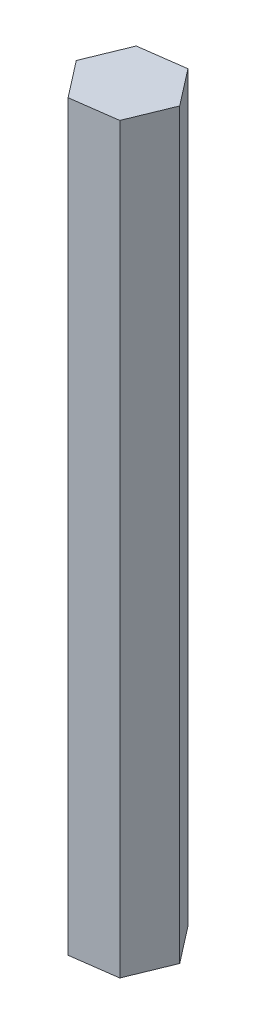
SolidWorks part; units mm, degrees
ref_plane "Front" through (0, 0, 0) normal (0, 0, 1) x (1, 0, 0)
ref_plane "Top" through (0, 0, 0) normal (0, 1, 0) x (1, 0, 0)
ref_plane "Right" through (0, 0, 0) normal (1, 0, 0) x (0, 0, -1)
sketch "Sketch1" plane through (0, 0, 0) normal (0, 1, 0) x (1, 0, 0)
  line L1 (3.3658, -4.349) -> (5.4492, 0.7404)
  line L2 (5.4492, 0.7404) -> (2.0834, 5.0893)
  line L3 (2.0834, 5.0893) -> (-3.3658, 4.349)
  line L4 (-3.3658, 4.349) -> (-5.4492, -0.7404)
  line L5 (-5.4492, -0.7404) -> (-2.0834, -5.0893)
  line L6 (-2.0834, -5.0893) -> (3.3658, -4.349)
  circle A0 centre (0, 0) radius 4.7625 construction
  dimension "D1" = 9.525
extrude "Boss-Extrude1" add sketch "Sketch1" along normal mid plane 88.9
